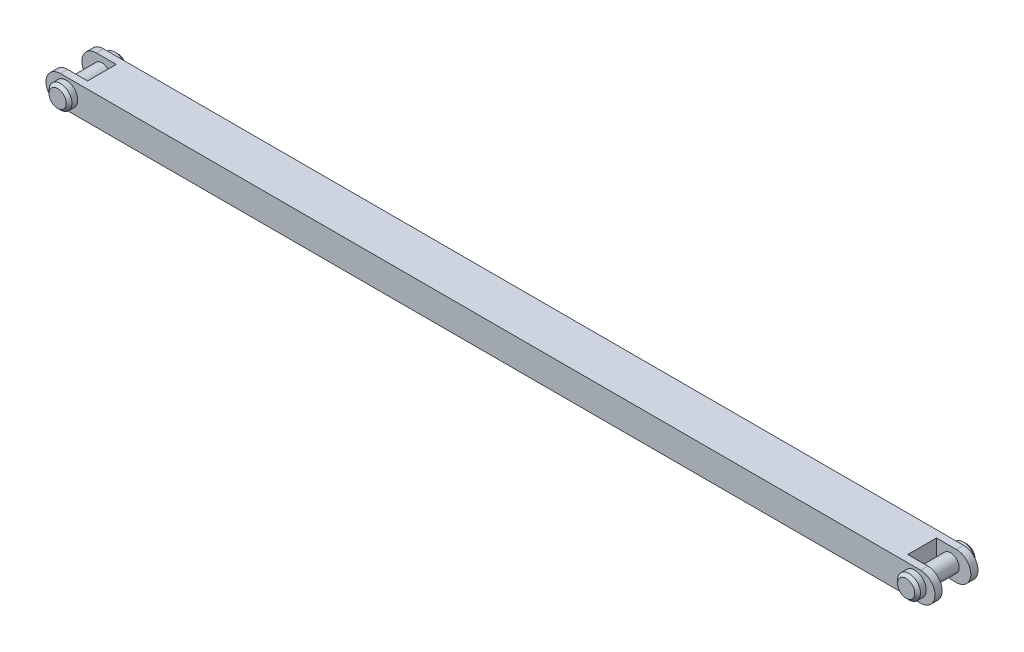
SolidWorks part; units mm, degrees
material "Alliage 1060"
ref_plane "Plan de face" through (0, 0, 0) normal (0, 0, 1) x (1, 0, 0)
ref_plane "Plan de dessus" through (0, 0, 0) normal (0, 1, 0) x (1, 0, 0)
ref_plane "Plan de droite" through (0, 0, 0) normal (1, 0, 0) x (0, 0, -1)
sketch "Esquisse1" plane through (0, 0, 0) normal (0, 0, 1) x (1, 0, 0)
  line L1 (5, 0) -> (305, 0)
  line L3 (5, 10) -> (305, 10)
  arc A0 (5, 0) -> (5, 10) centre (5, 5) cw
  arc A1 (305, 0) -> (305, 10) centre (305, 5) ccw
  dimension "D1" = 300
  dimension "D2" = 10
extrude "Boss.-Extru.1" add sketch "Esquisse1" along normal blind 15
sketch "Esquisse2" plane through (0, 10, 0) normal (0, 1, 0) x (1, 0, 0)
  line L0 (0, 0) -> (0, -15) construction
  line L1 (0, -2.5) -> (12, -2.5)
  line L2 (0, -2.5) -> (0, -12.5)
  line L3 (0, -12.5) -> (12, -12.5)
  line L4 (12, -2.5) -> (12, -12.5)
  line L5 (305, 0) -> (5, 0) construction
  line L6 (305, -15) -> (5, -15) construction
  line L7 (155, 0) -> (155, -15) construction
  line L8 (310, -12.5) -> (298, -12.5)
  line L9 (310, -2.5) -> (310, -12.5)
  line L10 (310, -2.5) -> (298, -2.5)
  line L11 (298, -2.5) -> (298, -12.5)
  point P10 (12, -7.5)
  dimension "D1" = 2.5
  dimension "D2" = 2.5
  dimension "D3" = 12
extrude "Enlèv. mat.-Extru.1" cut sketch "Esquisse2" against normal up to next
sketch "Esquisse3" plane through (0, 0, 2.5) normal (0, 0, 1) x (1, 0, 0)
  line L0 (155, 10) -> (155, 0) construction
  line L1 (305, 10) -> (5, 10) construction
  line L2 (5, 0) -> (305, 0) construction
  line L3 (155, 5) -> (-12.5681, 5) construction
  circle A0 centre (7.0549, 5) radius 3
  arc A1 (5, 10) -> (5, 0) centre (5, 5) ccw construction
  circle A2 centre (302.9451, 5) radius 3
  dimension "D1" = 6
  dimension "D2" = 2.0549
extrude "Boss.-Extru.2" add sketch "Esquisse3" along normal up to next
sketch "Esquisse4" plane through (0, 0, 15) normal (0, 0, 1) x (1, 0, 0)
  circle A0 centre (7.0549, 5) radius 4
  circle A1 centre (302.9451, 5) radius 4
  dimension "D1" = 8
  dimension "D2" = 8
extrude "Boss.-Extru.3" add sketch "Esquisse4" along normal blind 3
chamfer "Chanfrein1" distance 1 angle 45 2 edges at (306.9451, 5, 18) (11.0549, 5, 18)
sketch "Esquisse6" plane through (0, 10, 0) normal (0, 1, 0) x (1, 0, 0)
  line L0 (12, -7.5) -> (298, -7.5) construction
  line L1 (12, -12.5) -> (12, -2.5) construction
  line L2 (298, -2.5) -> (298, -12.5) construction
ref_plane "Plan1" through (0, 0, 7.5) normal (0, 0, 1) x (1, 0, 0)
mirror "Symétrie1" about plane through (0, 0, 7.5) normal (0, 0, 1) of "Chanfrein1", "Boss.-Extru.3"
